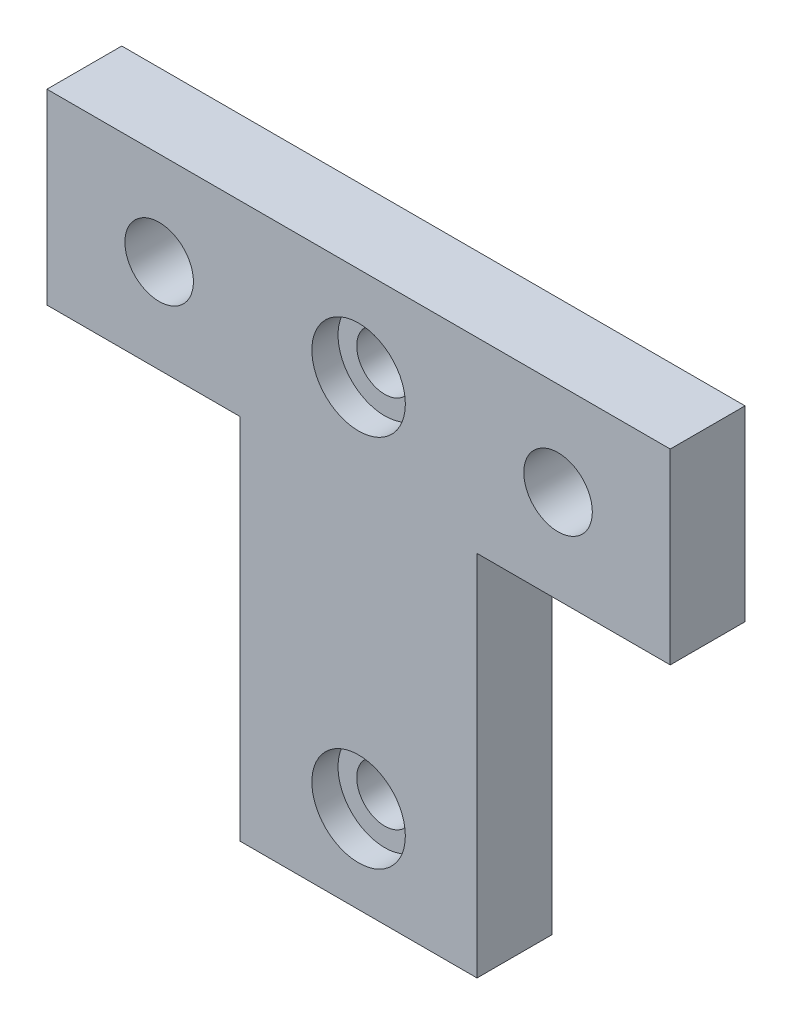
SolidWorks part; units mm, degrees
ref_plane "Front Plane" through (0, 0, 0) normal (0, 0, 1) x (1, 0, 0)
ref_plane "Top Plane" through (0, 0, 0) normal (0, 1, 0) x (1, 0, 0)
ref_plane "Right Plane" through (0, 0, 0) normal (1, 0, 0) x (0, 0, -1)
sketch "Sketch7" plane through (0, 0, 0) normal (0, 0, 1) x (1, 0, 0)
  line L0 (-25, -7.5) -> (25, -7.5)
  line L1 (25, -7.5) -> (25, 7.5)
  line L2 (25, 7.5) -> (-25, 7.5)
  line L3 (-25, 7.5) -> (-25, -7.5)
  line L5 (-9.5, -7.5) -> (9.5, -7.5)
  line L6 (-9.5, -7.5) -> (-9.5, -37)
  line L7 (-9.5, -37) -> (9.5, -37)
  line L8 (9.5, -7.5) -> (9.5, -37)
  circle A0 centre (16, 0) radius 2.75
  circle A1 centre (-16, 0) radius 2.75
  circle A2 centre (0, 0) radius 2.25
  circle A3 centre (0, -30) radius 2.25
  point P13 (0, -37)
  point P14 (0, -7.5)
  point P15 (-25, 0)
  dimension "D1" = 5.5
  dimension "D3" = 4.5
  dimension "D9" = 7
  dimension "D2" = 32
  dimension "D4" = 50
  dimension "D5" = 19
  dimension "D6" = 15
  dimension "D7" = 16
  dimension "D8" = 30
extrude "Boss-Extrude3" add sketch "Sketch7" along normal blind 6 contours L2 L3 L0 L1 A2 A1 A0 | L8 L0 L6 L7 A3
sketch "Sketch8" plane through (0, 0, 6) normal (0, 0, 1) x (1, 0, 0)
  circle A0 centre (0, 0) radius 3.75
  circle A1 centre (0, -30) radius 3.75
  dimension "D1" = 7.5
extrude "Cut-Extrude4" cut sketch "Sketch8" against normal blind 2.1
